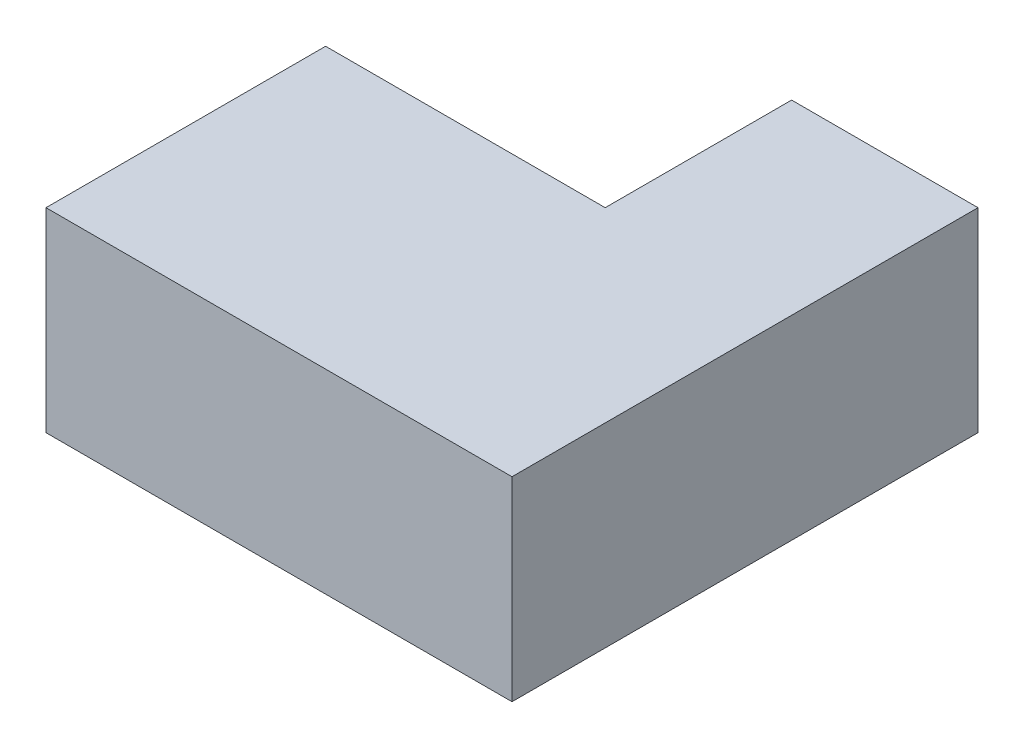
SolidWorks part; units mm, degrees
ref_plane "Front Plane" through (0, 0, 0) normal (0, 0, 1) x (1, 0, 0)
ref_plane "Top Plane" through (0, 0, 0) normal (0, 1, 0) x (1, 0, 0)
ref_plane "Right Plane" through (0, 0, 0) normal (1, 0, 0) x (0, 0, -1)
sketch "Sketch2" plane through (0, 0, 0) normal (0, 1, 0) x (1, 0, 0)
  line L0 (0, 0) -> (1270, 0)
  line L1 (1270, 0) -> (1270, 1270)
  line L2 (1270, 1270) -> (762, 1270)
  line L3 (762, 1270) -> (762, 762)
  line L4 (762, 762) -> (0, 762)
  line L5 (0, 762) -> (0, 0)
  point P9 (798.0585, 747.6827)
  dimension "D1" = 1270
  dimension "D2" = 762
  dimension "D3" = 508
  dimension "D4" = 508
extrude "Boss-Extrude1" add sketch "Sketch2" along normal mid plane 531.114
